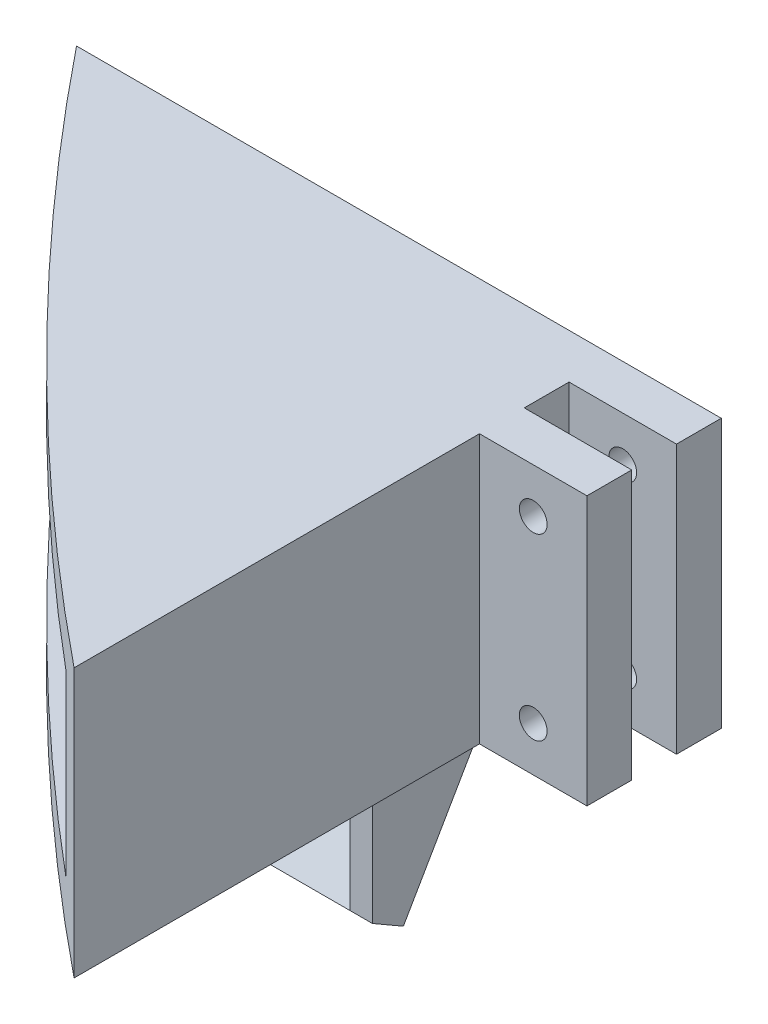
SolidWorks part; units mm, degrees
other "标注1"
sketch "草图28" plane through (2, -23.3827, 0) normal (0.0282, -0.8647, -0.5015) x (-0.6544, 0.3633, -0.6631)
ref_plane "前视基准面" through (0, 0, 0) normal (0, 0, 1) x (1, 0, 0)
ref_plane "上视基准面" through (0, 0, 0) normal (0, 1, 0) x (1, 0, 0)
ref_plane "右视基准面" through (0, 0, 0) normal (1, 0, 0) x (0, 0, -1)
sketch "草图1" plane through (0, 0, 0) normal (0, 1, 0) x (1, 0, 0)
  line L0 (0, 0) -> (-70, 0)
  line L2 (0, 0) -> (0, -5)
  line L3 (0, -5) -> (-10, -5)
  line L4 (-10, -5) -> (-10, -10)
  line L5 (-10, -10) -> (0, -10)
  line L6 (0, -10) -> (0, -15)
  line L7 (0, -15) -> (-10, -15)
  line L8 (-10, -15) -> (-10, -60.2761)
  arc A0 (-70, 0) -> (-10, -60.2761) centre (241.8847, 250.4554) ccw
  dimension "D3" = 400
  dimension "D1" = 70
  dimension "D2" = 61.1
  dimension "D4" = 5
  dimension "D5" = 5
  dimension "D6" = 5
  dimension "D7" = 10
extrude "凸台-拉伸1" add sketch "草图1" along normal blind 30
sketch "草图2" plane through (0, 0, 0) normal (0, 0, -1) x (-1, 0, 0)
  line L0 (0, 15) -> (23.3117, 15) construction
  line L1 (0, 30) -> (0, 0) construction
  line L2 (0, 30) -> (70, 30) construction
  circle A0 centre (4, 25) radius 1.55
  circle A1 centre (4, 5) radius 1.55
  dimension "D1" = 3.1
  dimension "D2" = 4
  dimension "D3" = 5
extrude "切除-拉伸1" cut sketch "草图2" against normal through all both and the other way through all
ref_plane "基准面11" through (0, 30, 0) normal (0, 1, 0) x (1, 0, 0)
sketch "草图6" plane through (0, 30, 0) normal (0, 1, 0) x (1, 0, 0)
  line L4 (-15, -15) -> (-15, -5)
  line L5 (-59.3918, -5) -> (-65.918, -5)
  line L6 (-15, -49.6033) -> (-15, -15)
  line L7 (0, -5) -> (-59.3918, -5)
  line L8 (-15, -49.6033) -> (-15, -15)
  line L9 (-15, -5) -> (-59.3918, -5)
  line L10 (-15, -49.6033) -> (-15, -56.1555)
  arc A2 (-70, 0) -> (-10, -60.2761) centre (241.8847, 250.4554) ccw construction
  arc A3 (-59.3918, -5) -> (-15, -49.6033) centre (241.8847, 250.4554) ccw
  arc A7 (-70, 0) -> (-10, -60.2761) centre (241.8847, 250.4554) ccw
  arc A8 (-65.918, -5) -> (-15, -56.1555) centre (241.8847, 250.4554) ccw
  dimension "D2" = 0
  dimension "D1" = 5
ref_plane "基准面15" through (0, 15, 0) normal (0, 1, 0) x (1, 0, 0)
sketch "草图9" plane through (0, 15, 0) normal (0, 1, 0) x (1, 0, 0)
  line L10 (-65.918, -5) -> (-59.3918, -5)
  line L11 (-15, -49.6033) -> (-15, -56.1555)
  line L12 (-15, -49.6033) -> (-15, -15)
  line L13 (0, -5) -> (-59.3918, -5)
  line L14 (-15, -49.6033) -> (-15, -15)
  line L15 (-15, -5) -> (-59.3918, -5)
  line L16 (-15, -15) -> (-15, -5)
  arc A2 (-59.3918, -5) -> (-15, -49.6033) centre (241.8847, 250.4554) ccw
  arc A5 (-65.918, -5) -> (-15, -56.1555) centre (241.8847, 250.4554) ccw
  arc A6 (-65.918, -5) -> (-15, -56.1555) centre (241.8847, 250.4554) ccw
  dimension "D2" = 0
  dimension "D1" = 5
extrude "切除-拉伸6" cut sketch "草图9" against normal mid plane 20
sketch "草图11" plane through (0, 15, 0) normal (0, 1, 0) x (1, 0, 0)
  line L0 (-15, -5) -> (-23, -5)
  line L1 (-15, -5) -> (-59.3918, -5) construction
  line L2 (-15, -5) -> (-15, -10)
  line L3 (-15, -15) -> (-15, -5) construction
  line L4 (-15, -10) -> (-23, -5)
  dimension "D1" = 8
  dimension "D2" = 5
extrude "凸台-拉伸3" add sketch "草图11" along normal mid plane 25
ref_plane "基准面16" through (0, 0, 0) normal (0, 0, -1) x (-1, 0, 0)
sketch "草图12" plane through (0, 0, 0) normal (1, 0, 0) x (0, 0, -1)
  line L1 (-15, 30) -> (-10, 30)
  line L2 (-15, 30) -> (-15, 0)
  line L3 (-15, 0) -> (-10, 0)
  line L4 (-10, 30) -> (-10, 0)
  line L5 (-5, 0) -> (0, 0)
  line L6 (-5, 0) -> (-5, 30)
  line L7 (-5, 30) -> (0, 30)
  line L8 (0, 0) -> (0, 30)
extrude "凸台-拉伸4" add sketch "草图12" along normal blind 2
sketch "草图17" plane through (0, 0, 0) normal (0, -1, 0) x (1, 0, 0)
  line L0 (2, 0) -> (-70, 0) construction
  line L1 (-45, 0) -> (-20, 0)
  line L2 (-45, 0) -> (-45, 25)
  line L3 (-45, 25) -> (-20, 25)
  line L4 (-20, 0) -> (-20, 25)
  dimension "D1" = 25
extrude "凸台-拉伸7" [suppressed] add sketch "草图17" along normal blind 40
sketch "草图18" [suppressed] plane through (-45, 0, 0) normal (-1, 0, 0) x (0, 0, 1)
  line L10 (0, 0) -> (25, -40)
  line L11 (25, -40) -> (0, -40)
  line L12 (25, -40) -> (0, -40) construction
  line L13 (0, -40) -> (0, 0)
extrude "切除-拉伸9" [suppressed] cut sketch "草图18" against normal blind 50
sketch "草图21" [suppressed] plane through (0, 0, 0) normal (0, -0.53, -0.848) x (-1, 0, 0)
  line L0 (20, -47.1699) -> (20, 0) construction
  line L1 (20, -47.1699) -> (45, -47.1699) construction
  circle A0 centre (32.5, -22.1699) radius 1.5
  circle A1 centre (32.5, -12.1699) radius 1.5
  circle A2 centre (32.5, -32.1699) radius 1.5
  dimension "D1" = 12.5
  dimension "D3" = 10
  dimension "D2" = 25
  dimension "D4" = 10
extrude "切除-拉伸12" [suppressed] cut sketch "草图21" against normal blind 7
sketch "草图22" [suppressed] plane through (-45, 0, 0) normal (-1, 0, 0) x (0, 0, 1)
  line L0 (7.217, -4) -> (21, -4)
  line L1 (21, -4) -> (21, -26.0528)
  line L2 (21, -26.0528) -> (7.217, -4)
  line L4 (25, 0) -> (0, 0) construction
  line L5 (25, -40) -> (0, 0) construction
  line L6 (0, 0) -> (60.2761, 0) construction
  line L7 (25, -40) -> (25, 0) construction
  dimension "D1" = 4
  dimension "D2" = 4
  dimension "D3" = 4
extrude "切除-拉伸13" [suppressed] cut sketch "草图22" against normal blind 500
sketch "草图23" [suppressed] plane through (0, 0, 25) normal (0, 0, 1) x (1, 0, 0)
  line L0 (-20, 0) -> (-45, 0) construction
  line L1 (-41, -4) -> (-24, -4)
  line L2 (-41, -4) -> (-41, -25)
  line L3 (-41, -25) -> (-24, -25)
  line L4 (-24, -4) -> (-24, -25)
  line L5 (-45, -40) -> (-45, 0) construction
  line L6 (-20, -40) -> (-20, 0) construction
  line L7 (-20, -40) -> (-45, -40) construction
  dimension "D1" = 4
  dimension "D2" = 4
  dimension "D3" = 4
  dimension "D4" = 15
extrude "切除-拉伸14" [suppressed] cut sketch "草图23" against normal blind 4
ref_plane "基准面17" through (0, 0, 0) normal (0, -0.5, -0.866) x (-1, 0, 0)
sketch "草图24" plane through (0, 0, 0) normal (0, -0.5, -0.866) x (-1, 0, 0)
  line L0 (-2, 0) -> (70, 0) construction
  line L1 (20, 0) -> (42, 0)
  line L2 (10, -5) -> (10, -2.5) construction
  line L3 (20, 0) -> (42, 0)
  line L4 (20, 0) -> (20, -27)
  line L5 (20, -27) -> (42, -27)
  line L6 (42, 0) -> (42, -27)
  line L7 (28, 0) -> (28, -27) construction
  line L8 (28, -15) -> (38, -15) construction
  line L9 (28, -15) -> (36.6603, -10) construction
  line L10 (28, -15) -> (33, -6.3397) construction
  line L11 (28, -15) -> (36.6603, -20) construction
  line L12 (28, -15) -> (33, -23.6603) construction
  circle A0 centre (28, -15) radius 1.55
  circle A1 centre (28, -15) radius 10 construction
  circle A2 centre (33, -6.3397) radius 1.55
  circle A3 centre (36.6603, -10) radius 1.55
  circle A4 centre (38, -15) radius 1.55
  circle A5 centre (36.6603, -20) radius 1.55
  circle A6 centre (33, -23.6603) radius 1.55
  dimension "D5" = 3.1
  dimension "D6" = 20
  dimension "D1" = 22
  dimension "D2" = 27
  dimension "D3" = 10
  dimension "D4" = 8
  dimension "D7" = 30
  dimension "D8" = 12
extrude "凸台-拉伸8" add sketch "草图24" against normal blind 4 contours L6 L1 L4 L5 A6 A5 A4 A3 A2 A0
sketch "草图25" plane through (-20, 0, 0) normal (1, 0, 0) x (0, 0, -1)
  line L0 (-16.9641, -21.3827) -> (-16.9641, 0)
  line L1 (-60.2761, 0) -> (-15, 0) construction
  line L2 (-16.9641, 0) -> (-4.6188, 0)
  line L3 (-16.9641, -21.3827) -> (-4.6188, 0)
extrude "凸台-拉伸9" add sketch "草图25" against normal blind 2.5
sketch "草图27" plane through (-42, 0, 0) normal (-1, 0, 0) x (0, 0, 1)
  line L0 (0, 0) -> (16.9641, 0)
  line L1 (16.9641, 0) -> (16.9641, -21.3827)
  line L2 (16.9641, -21.3827) -> (13.5, -23.3827)
  line L3 (13.5, -23.3827) -> (0, 0)
extrude "凸台-拉伸10" add sketch "草图27" along normal blind 2.5
